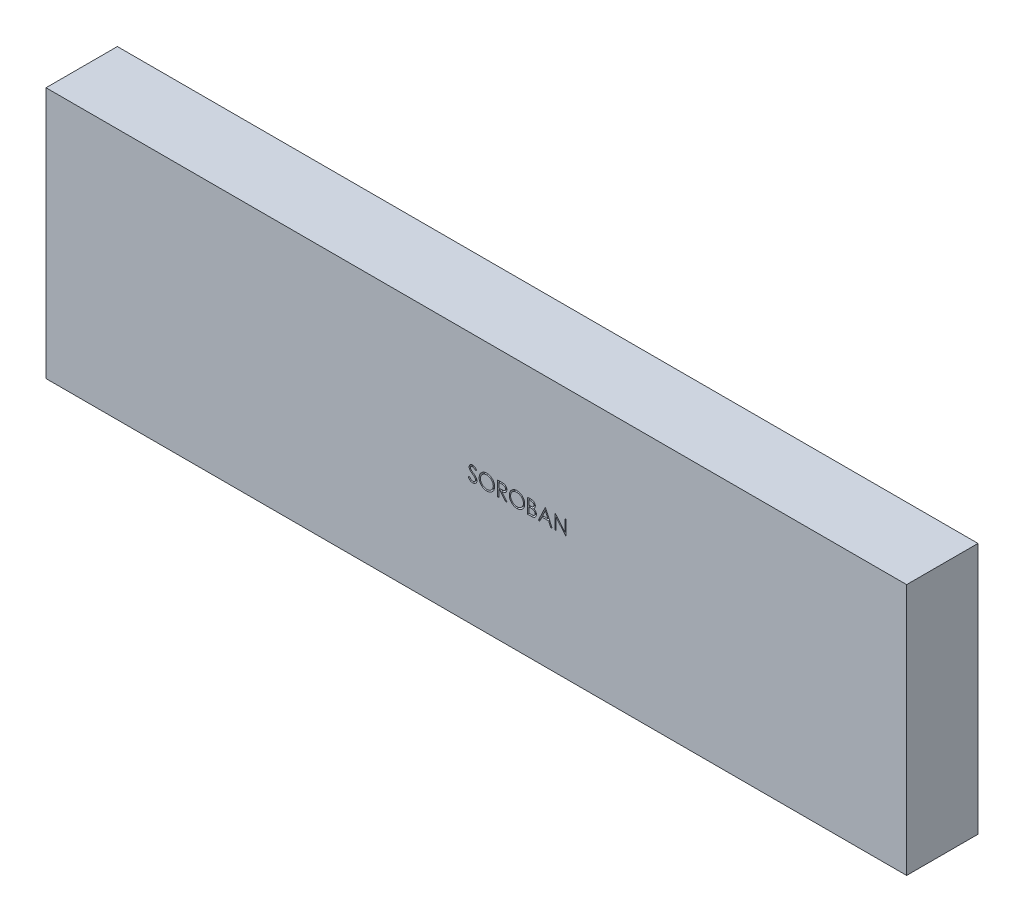
SolidWorks part; units mm, degrees
ref_plane "正面" through (0, 0, 0) normal (0, 0, 1) x (1, 0, 0)
ref_plane "平面" through (0, 0, 0) normal (0, 1, 0) x (1, 0, 0)
ref_plane "右側面" through (0, 0, 0) normal (1, 0, 0) x (0, 0, -1)
sketch "ｽｹｯﾁ1" plane through (0, 0, 0) normal (0, 0, 1) x (1, 0, 0)
  line L1 (-102.5, -30) -> (102.5, -30)
  line L2 (-102.5, -30) -> (-102.5, 30)
  line L3 (-102.5, 30) -> (102.5, 30)
  line L4 (102.5, -30) -> (102.5, 30)
  line L5 (-102.5, -30) -> (102.5, 30) construction
  line L6 (-102.5, 30) -> (102.5, -30) construction
  point P0 (0, 0)
  dimension "D1" = 205
  dimension "D2" = 60
extrude "ﾎﾞｽ - 押し出し1" add sketch "ｽｹｯﾁ1" along normal blind 17
sketch "ｽｹｯﾁ2" plane through (0, 0, 17) normal (0, 0, 1) x (1, 0, 0)
  text T0 "SOROBAN"
extrude "ｶｯﾄ - 押し出し1" cut sketch "ｽｹｯﾁ2" against normal blind 5
